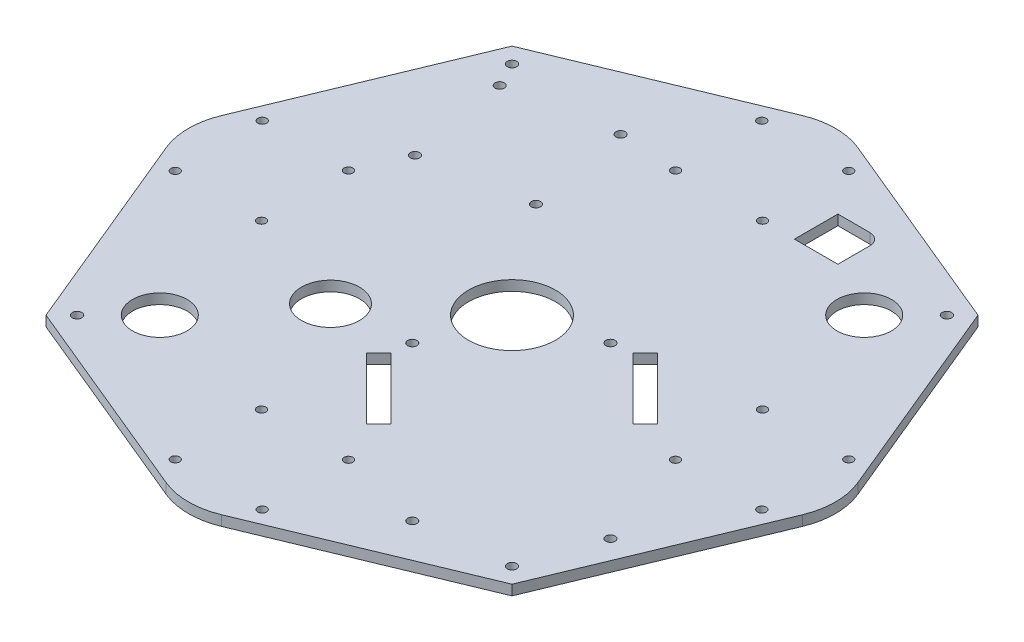
SolidWorks part; units mm, degrees
ref_plane "Front Plane" through (0, 0, 0) normal (0, 0, 1) x (1, 0, 0)
ref_plane "Top Plane" through (0, 0, 0) normal (0, 1, 0) x (1, 0, 0)
ref_plane "Right Plane" through (0, 0, 0) normal (1, 0, 0) x (0, 0, -1)
sketch "Sketch1" plane through (0, 0, 0) normal (0, 1, 0) x (1, 0, 0)
  line L0 (0, -113.6512) -> (80.3635, -80.3635)
  line L7 (0, 113.6512) -> (-80.3635, 80.3635)
  line L8 (-80.3635, 80.3635) -> (-113.6512, 0)
  line L9 (-113.6512, 0) -> (-80.3635, -80.3635)
  line L10 (-80.3635, -80.3635) -> (0, -113.6512)
  line L11 (80.3635, -80.3635) -> (113.6512, 0)
  line L12 (113.6512, 0) -> (80.3635, 80.3635)
  line L13 (80.3635, 80.3635) -> (0, 113.6512)
  circle A0 centre (0, 0) radius 105 construction
  dimension "D1" = 210
extrude "Boss-Extrude2" add sketch "Sketch1" along normal blind 3.5
sketch "Sketch3" plane through (0, 3.5, 0) normal (0, 1, 0) x (1, 0, 0)
  line L0 (-113.6512, 0) -> (113.6512, 0) construction
  line L1 (0, 113.6512) -> (0, -113.6512) construction
  line L2 (-75, -75) -> (0, 0) construction
  circle A0 centre (-75, -75) radius 1.625
  circle A1 centre (75, -75) radius 1.625
  circle A2 centre (75, 75) radius 1.625
  circle A3 centre (-75, 75) radius 1.625
  point P28 (0, 0)
  dimension "D1" = 3.25
  dimension "D2" = 150
extrude "Cut-Extrude3" cut sketch "Sketch3" against normal through all both and the other way through all
sketch "Sketch6" plane through (0, 3.5, 0) normal (0, 1, 0) x (1, 0, 0)
  circle A0 centre (0, 0) radius 15
  dimension "D1" = 30
extrude "Cut-Extrude6" cut sketch "Sketch6" against normal through all both and the other way through all
sketch "Sketch8" plane through (0, 3.5, 0) normal (0, 1, 0) x (1, 0, 0)
  line L0 (-15, -71.4012) -> (15, -71.4012) construction
  line L1 (15, -71.4012) -> (15, -101.1512) construction
  line L2 (15, -101.1512) -> (-15, -101.1512) construction
  line L3 (-15, -101.1512) -> (-15, -71.4012) construction
  line L4 (0, 0) -> (0, -71.4012) construction
  line L5 (0, -101.1512) -> (0, -113.6512) construction
  circle A0 centre (-15, -71.4012) radius 1.5
  circle A1 centre (15, -71.4012) radius 1.5
  circle A2 centre (-15, -101.1512) radius 1.5
  circle A3 centre (15, -101.1512) radius 1.5
  dimension "D1" = 3
  dimension "D2" = 29.75
  dimension "D3" = 30
  dimension "D4" = 12.5
extrude "Cut-Extrude7" cut sketch "Sketch8" against normal up to surface (3.5 mm away) up to face at (0, 0, 15)
pattern_circular "CirPattern1" count 4 over 360 about axis through (0, 0, 0) along (0, 1, 0) of "Cut-Extrude7"
sketch "Sketch20" plane through (0, 3.5, 0) normal (0, 1, 0) x (1, 0, 0)
  line L0 (15, 71.4012) -> (26, 71.4012) construction
  line L1 (41, 71.4012) -> (26, 71.4012)
  line L2 (41, 71.4012) -> (41, 86.4012)
  line L3 (41, 86.4012) -> (26, 86.4012)
  line L4 (26, 71.4012) -> (26, 86.4012)
  dimension "D1" = 15
  dimension "D2" = 15
  dimension "D3" = 11
extrude "Cut-Extrude12" cut sketch "Sketch20" against normal through all both and the other way through all
fillet "Fillet2" radius 25 4 edges at (-113.6512, 1.75, 0) (0, 1.75, -113.6512) (113.6512, 1.75, 0) (0, 1.75, 113.6512)
fillet "Fillet3" radius 4 1 edges at (41, 1.75, -86.4012)
sketch "Sketch21" plane through (0, 0, 0) normal (0, -1, 0) x (1, 0, 0)
  circle A0 centre (-8.868, 25.5252) radius 2.5
  circle A1 centre (25.3109, -8.6536) radius 2.5
  circle A2 centre (44.2592, 78.6524) radius 2.5
  circle A3 centre (83.7364, 49.7719) radius 2.5
  dimension "D1" = 5
extrude "Boss-Extrude4" add sketch "Sketch21" along normal blind 3
sketch "Sketch22" plane through (0, -3, 0) normal (0, -1, 0) x (1, 0, 0)
  circle A0 centre (83.7364, 49.7719) radius 1.6
  circle A1 centre (25.3109, -8.6536) radius 1.6
  circle A2 centre (-8.868, 25.5252) radius 1.6
  circle A3 centre (44.2592, 78.6524) radius 1.6
  dimension "D1" = 3.2
extrude "Cut-Extrude13" cut sketch "Sketch22" against normal through all
sketch "Sketch24" plane through (0, 0, 0) normal (0, -1, 0) x (1, 0, 0)
  line L0 (-64.4726, -31.0268) -> (-29.0195, -37.2781) construction
  line L1 (-29.0195, -37.2781) -> (-35.2708, -72.7312) construction
  line L2 (-35.2708, -72.7312) -> (-70.7239, -66.4799) construction
  line L3 (-70.7239, -66.4799) -> (-64.4726, -31.0268) construction
  line L4 (-52.9974, -69.6055) -> (-73.0875, -66.0631) construction
  line L5 (-52.9974, -69.6055) -> (-32.9073, -73.148) construction
  line L6 (-64.4726, -31.0268) -> (-64.0558, -28.6633) construction
  line L7 (-29.0195, -37.2781) -> (-28.6027, -34.9146) construction
  circle A0 centre (-64.4726, -31.0268) radius 2.4
  circle A1 centre (-29.0195, -37.2781) radius 2.4
  circle A2 centre (-35.2708, -72.7312) radius 2.4
  circle A3 centre (-70.7239, -66.4799) radius 2.4
  dimension "D2" = 4.8
  dimension "D1" = 36
extrude "Boss-Extrude6" add sketch "Sketch24" along normal blind 3.5
sketch "Sketch25" plane through (0, -3.5, 0) normal (0, -1, 0) x (1, 0, 0)
  circle A0 centre (-29.0195, -37.2781) radius 1.6
  circle A1 centre (-64.4726, -31.0268) radius 1.6
  circle A2 centre (-70.7239, -66.4799) radius 1.6
  circle A3 centre (-35.2708, -72.7312) radius 1.6
  dimension "D1" = 3.2
extrude "Cut-Extrude14" cut sketch "Sketch25" against normal through all both and the other way through all
sketch "Sketch26" plane through (0, 0, 0) normal (0, -1, 0) x (1, 0, 0)
  line L0 (-80.3635, 80.3635) -> (0, 0) construction
  circle A0 centre (-60.7414, 60.7414) radius 9.4046
  circle A2 centre (60.7414, -60.7414) radius 9.4046
  point P10 (0, 0)
  point P11 (0, 0)
  dimension "D1" = 2
extrude "Cut-Extrude15" cut sketch "Sketch26" against normal through all both and the other way through all
sketch "Sketch27" plane through (0, 0, 0) normal (0, -1, 0) x (1, 0, 0)
  line L0 (7.3995, 57.5539) -> (11.6422, 53.3112)
  line L1 (11.6422, 53.3112) -> (-9.571, 32.098)
  line L2 (-9.571, 32.098) -> (-13.8137, 36.3407)
  line L3 (-13.8137, 36.3407) -> (7.3995, 57.5539)
  line L4 (0, 0) -> (80.3635, 80.3635) construction
  line L5 (32.098, -9.571) -> (36.3407, -13.8137)
  line L6 (53.3112, 11.6422) -> (32.098, -9.571)
  line L7 (57.5539, 7.3995) -> (53.3112, 11.6422)
  line L8 (36.3407, -13.8137) -> (57.5539, 7.3995)
  dimension "D1" = 30
  dimension "D2" = 6
extrude "Cut-Extrude16" cut sketch "Sketch27" against normal through all both and the other way through all
sketch "Sketch28" plane through (0, 3.5, 0) normal (0, 1, 0) x (1, 0, 0)
  circle A0 centre (-34.6949, -27.9178) radius 10
  dimension "D1" = 20
extrude "Cut-Extrude17" cut sketch "Sketch28" against normal through all both and the other way through all
